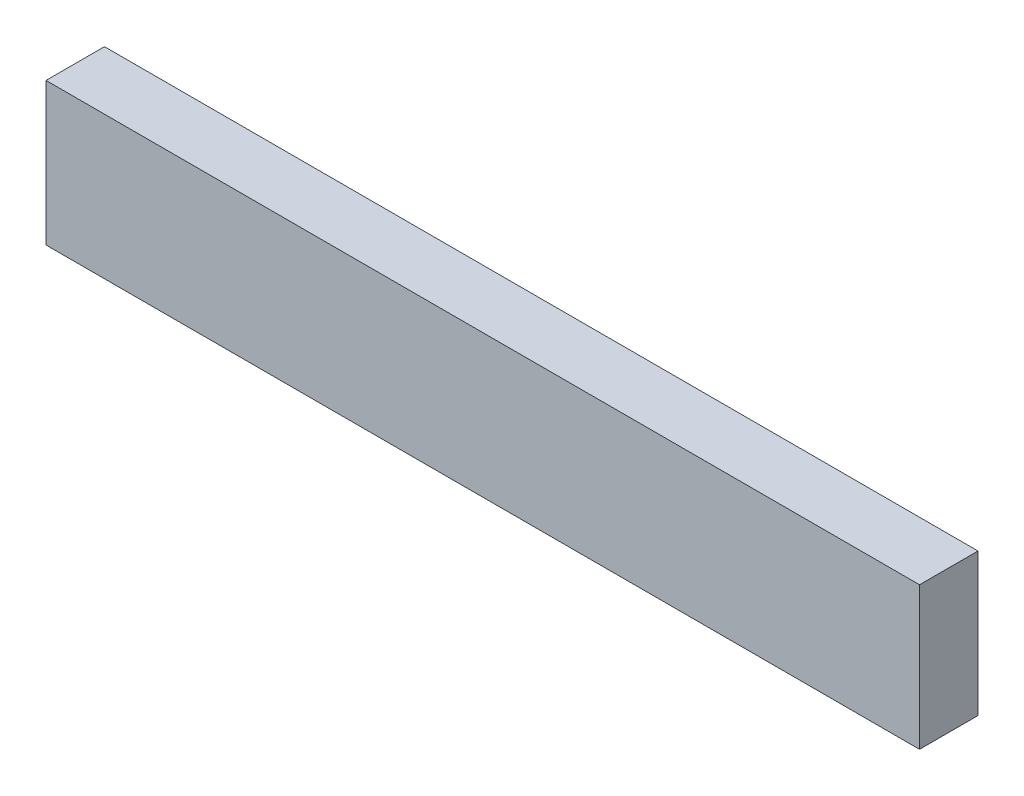
SolidWorks part; units mm, degrees
ref_plane "Спереди" through (0, 0, 0) normal (0, 0, 1) x (1, 0, 0)
ref_plane "Сверху" through (0, 0, 0) normal (0, 1, 0) x (1, 0, 0)
ref_plane "Справа" through (0, 0, 0) normal (1, 0, 0) x (0, 0, -1)
sketch "Эскиз1" plane through (0, 0, 0) normal (0, 0, 1) x (1, 0, 0)
  line L1 (-23.9, -3.9) -> (23.9, -3.9)
  line L2 (-23.9, -3.9) -> (-23.9, 3.9)
  line L3 (-23.9, 3.9) -> (23.9, 3.9)
  line L4 (23.9, -3.9) -> (23.9, 3.9)
  line L5 (-23.9, -3.9) -> (23.9, 3.9) construction
  line L6 (-23.9, 3.9) -> (23.9, -3.9) construction
  point P0 (0, 0)
  dimension "D1" = 47.8
  dimension "D2" = 7.8
extrude "Бобышка-Вытянуть1" add sketch "Эскиз1" along normal blind 3.2
sketch "Эскиз2" plane through (0, 0, 0) normal (0, 0, -1) x (-1, 0, 0)
  circle A0 centre (-20.4915, 0) radius 2.5
  circle A1 centre (-12.4915, 0) radius 2.5
  circle A2 centre (-4.4915, 0) radius 2.5
  circle A3 centre (3.5085, 0) radius 2.5
  circle A4 centre (11.5085, 0) radius 2.5
  circle A5 centre (19.5085, 0) radius 2.5
  dimension "D1" = 6
extrude "Вырез-Вытянуть1" cut sketch "Эскиз2" against normal blind 1.8
